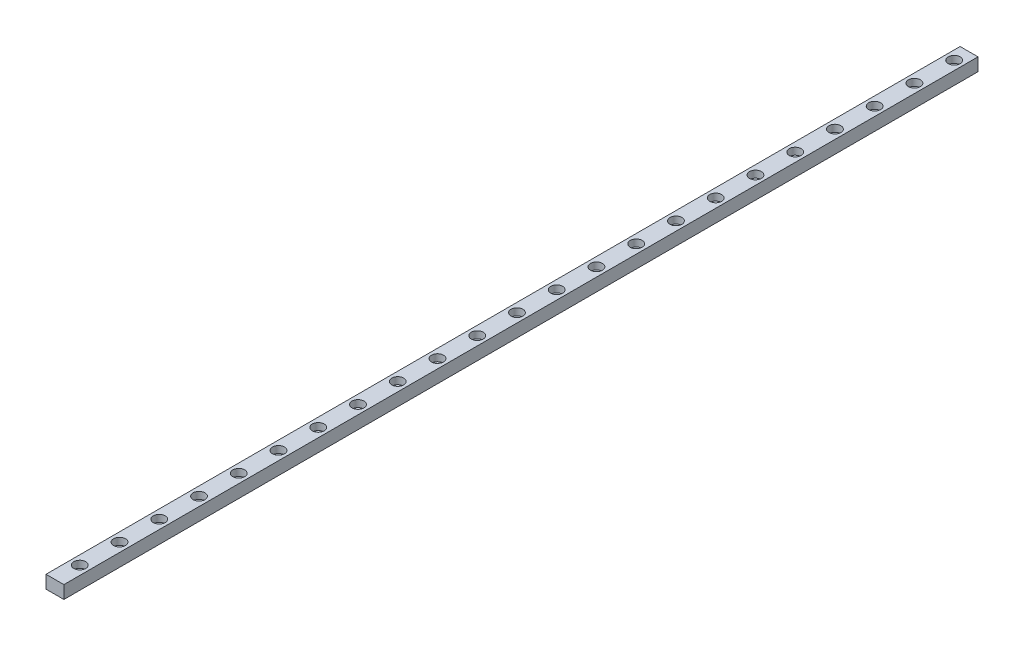
SolidWorks part; units mm, degrees
material "AISI 304"
ref_plane "前视基准面" through (0, 0, 0) normal (0, 0, 1) x (1, 0, 0)
ref_plane "上视基准面" through (0, 0, 0) normal (0, 1, 0) x (1, 0, 0)
ref_plane "右视基准面" through (0, 0, 0) normal (1, 0, 0) x (0, 0, -1)
sketch "草图1" plane through (0, 0, -89.2648) normal (0, 0, 1) x (1, 0, 0)
  line L1 (-4.5, -3.25) -> (4.5, -3.25)
  line L2 (-4.5, -3.25) -> (-4.5, 3.25)
  line L3 (-4.5, 3.25) -> (4.5, 3.25)
  line L4 (4.5, -3.25) -> (4.5, 3.25)
  line L5 (-4.5, -3.25) -> (4.5, 3.25) construction
  line L6 (-4.5, 3.25) -> (4.5, -3.25) construction
  point P0 (0, 0)
  dimension "D1" = 9
  dimension "D2" = 6.5
extrude "凸台-拉伸1" add sketch "草图1" along normal blind 460
sketch "草图2" plane through (0, 3.25, 0) normal (0, 1, 0) x (1, 0, 0)
  line L0 (0, 0) -> (0, -499.5684) construction
  line L1 (4.5, 89.2648) -> (-4.5, 89.2648) construction
  circle A0 centre (0, 81.7648) radius 1.75
  circle A1 centre (0, 61.7648) radius 1.75
  circle A2 centre (0, 41.7648) radius 1.75
  circle A3 centre (0, 21.7648) radius 1.75
  circle A4 centre (0, 1.7648) radius 1.75
  circle A5 centre (0, -18.2352) radius 1.75
  circle A6 centre (0, -38.2352) radius 1.75
  circle A7 centre (0, -58.2352) radius 1.75
  circle A8 centre (0, -78.2352) radius 1.75
  circle A9 centre (0, -98.2352) radius 1.75
  circle A10 centre (0, -118.2352) radius 1.75
  circle A11 centre (0, -138.2352) radius 1.75
  circle A12 centre (0, -158.2352) radius 1.75
  circle A13 centre (0, -178.2352) radius 1.75
  circle A14 centre (0, -198.2352) radius 1.75
  circle A15 centre (0, -218.2352) radius 1.75
  circle A16 centre (0, -238.2352) radius 1.75
  circle A17 centre (0, -258.2352) radius 1.75
  circle A18 centre (0, -278.2352) radius 1.75
  circle A19 centre (0, -298.2352) radius 1.75
  circle A20 centre (0, -318.2352) radius 1.75
  circle A21 centre (0, -338.2352) radius 1.75
  circle A22 centre (0, -358.2352) radius 1.75
  circle A23 centre (0, -378.2352) radius 1.75
  circle A24 centre (0, -398.2352) radius 1.75
  circle A25 centre (0, -418.2352) radius 1.75
  circle A26 centre (0, -438.2352) radius 1.75
  circle A27 centre (0, -458.2352) radius 1.75
  circle A28 centre (0, -478.2352) radius 1.75
  circle A29 centre (0, -498.2352) radius 1.75
  circle A30 centre (0, -518.2352) radius 1.75
  circle A31 centre (0, -538.2352) radius 1.75
  circle A32 centre (0, -558.2352) radius 1.75
  circle A33 centre (0, -578.2352) radius 1.75
  circle A34 centre (0, -598.2352) radius 1.75
  circle A35 centre (0, -618.2352) radius 1.75
  circle A36 centre (0, -638.2352) radius 1.75
  circle A37 centre (0, -658.2352) radius 1.75
  circle A38 centre (0, -678.2352) radius 1.75
  circle A39 centre (0, -698.2352) radius 1.75
  circle A40 centre (0, -718.2352) radius 1.75
  circle A41 centre (0, -738.2352) radius 1.75
  circle A42 centre (0, -758.2352) radius 1.75
  circle A43 centre (0, -778.2352) radius 1.75
  circle A44 centre (0, -798.2352) radius 1.75
  circle A45 centre (0, -818.2352) radius 1.75
  circle A46 centre (0, -838.2352) radius 1.75
  circle A47 centre (0, -858.2352) radius 1.75
  circle A48 centre (0, -878.2352) radius 1.75
  circle A49 centre (0, -898.2352) radius 1.75
  circle A50 centre (0, -918.2352) radius 1.75
  circle A51 centre (0, -938.2352) radius 1.75
  circle A52 centre (0, -958.2352) radius 1.75
  circle A53 centre (0, -978.2352) radius 1.75
  circle A54 centre (0, -998.2352) radius 1.75
  circle A55 centre (0, -1018.2352) radius 1.75
  circle A56 centre (0, -1038.2352) radius 1.75
  circle A57 centre (0, -1058.2352) radius 1.75
  circle A58 centre (0, -1078.2352) radius 1.75
  circle A59 centre (0, -1098.2352) radius 1.75
  dimension "D1" = 3.5
  dimension "D2" = 7.5
  dimension "D4" = 20
  dimension "D3" = 60
extrude "切除-拉伸1" cut sketch "草图2" against normal through all
sketch "草图3" plane through (0, 3.25, 0) normal (0, 1, 0) x (1, 0, 0)
  circle A0 centre (0, 81.7648) radius 3
  circle A1 centre (0, 61.7648) radius 3
  circle A2 centre (0, 41.7648) radius 3
  circle A3 centre (0, 21.7648) radius 3
  circle A4 centre (0, 1.7648) radius 3
  circle A5 centre (0, -18.2352) radius 3
  circle A6 centre (0, -38.2352) radius 3
  circle A7 centre (0, -58.2352) radius 3
  circle A8 centre (0, -78.2352) radius 3
  circle A9 centre (0, -98.2352) radius 3
  circle A10 centre (0, -118.2352) radius 3
  circle A11 centre (0, -138.2352) radius 3
  circle A12 centre (0, -158.2352) radius 3
  circle A13 centre (0, -178.2352) radius 3
  circle A14 centre (0, -198.2352) radius 3
  circle A15 centre (0, -218.2352) radius 3
  circle A16 centre (0, -238.2352) radius 3
  circle A17 centre (0, -258.2352) radius 3
  circle A18 centre (0, -278.2352) radius 3
  circle A19 centre (0, -298.2352) radius 3
  circle A20 centre (0, -318.2352) radius 3
  circle A21 centre (0, -338.2352) radius 3
  circle A22 centre (0, -358.2352) radius 3
  circle A23 centre (0, -378.2352) radius 3
  circle A24 centre (0, -398.2352) radius 3
  circle A25 centre (0, -418.2352) radius 3
  circle A26 centre (0, -438.2352) radius 3
  circle A27 centre (0, -458.2352) radius 3
  circle A28 centre (0, -478.2352) radius 3
  circle A29 centre (0, -498.2352) radius 3
  circle A30 centre (0, -518.2352) radius 3
  circle A31 centre (0, -538.2352) radius 3
  circle A32 centre (0, -558.2352) radius 3
  circle A33 centre (0, -578.2352) radius 3
  circle A34 centre (0, -598.2352) radius 3
  circle A35 centre (0, -618.2352) radius 3
  circle A36 centre (0, -638.2352) radius 3
  circle A37 centre (0, -658.2352) radius 3
  circle A38 centre (0, -678.2352) radius 3
  circle A39 centre (0, -698.2352) radius 3
  circle A40 centre (0, -718.2352) radius 3
  circle A41 centre (0, -738.2352) radius 3
  circle A42 centre (0, -758.2352) radius 3
  circle A43 centre (0, -778.2352) radius 3
  circle A44 centre (0, -798.2352) radius 3
  circle A45 centre (0, -818.2352) radius 3
  circle A46 centre (0, -838.2352) radius 3
  circle A47 centre (0, -858.2352) radius 3
  circle A48 centre (0, -878.2352) radius 3
  circle A49 centre (0, -898.2352) radius 3
  circle A50 centre (0, -918.2352) radius 3
  circle A51 centre (0, -938.2352) radius 3
  circle A52 centre (0, -958.2352) radius 3
  circle A53 centre (0, -978.2352) radius 3
  circle A54 centre (0, -998.2352) radius 3
  circle A55 centre (0, -1018.2352) radius 3
  circle A56 centre (0, -1038.2352) radius 3
  circle A57 centre (0, -1058.2352) radius 3
  circle A58 centre (0, -1078.2352) radius 3
  circle A59 centre (0, -1098.2352) radius 3
  dimension "D1" = 6
  dimension "D3" = 20
  dimension "D2" = 60
extrude "切除-拉伸2" cut sketch "草图3" against normal blind 3.5
